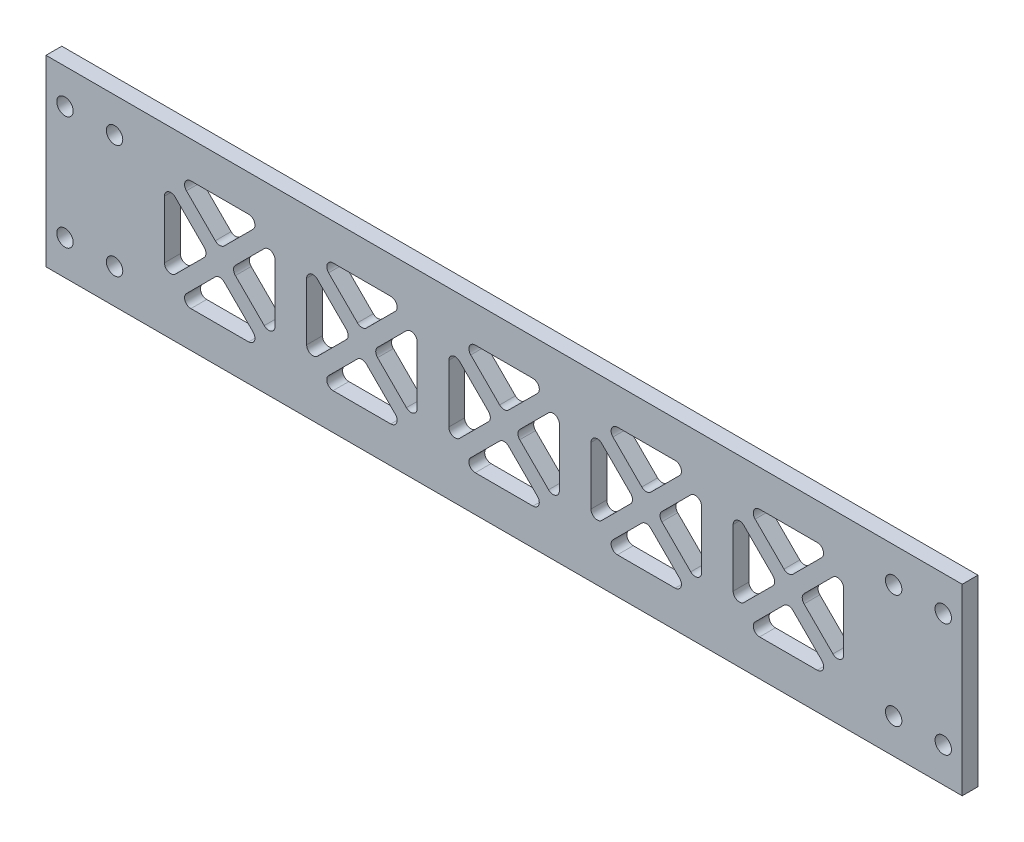
SolidWorks part; units mm, degrees
ref_plane "前视基准面" through (0, 0, 0) normal (0, 0, 1) x (1, 0, 0)
ref_plane "上视基准面" through (0, 0, 0) normal (0, 1, 0) x (1, 0, 0)
ref_plane "右视基准面" through (0, 0, 0) normal (1, 0, 0) x (0, 0, -1)
other "Configuration Table"
sketch "草图1" plane through (0, 0, 0) normal (0, 0, 1) x (1, 0, 0)
  line L1 (0, 0) -> (290, 0)
  line L2 (0, 0) -> (0, -58)
  line L3 (0, -58) -> (290, -58)
  line L4 (290, 0) -> (290, -58)
  dimension "D1" = 58
  dimension "D2" = 290
extrude "凸台-拉伸1" add sketch "草图1" along normal blind 5
sketch "草图2" plane through (0, 0, 5) normal (0, 0, 1) x (1, 0, 0)
  line L0 (145, 0) -> (145, -58)
  line L1 (0, -15) -> (-5, -15)
  line L2 (0, -15) -> (0, -43)
  line L3 (0, -43) -> (-5, -43)
  line L4 (0, 0) -> (0, -58)
  line L5 (0, -58) -> (290, -58)
  line L6 (290, -58) -> (290, 0)
  line L7 (290, 0) -> (0, 0)
  line L8 (0, 0) -> (0, -58)
  line L9 (0, -58) -> (290, -58)
  line L10 (290, -58) -> (290, 0)
  line L11 (290, 0) -> (0, 0)
  line L12 (-5, -15) -> (-5, -43)
  line L13 (290, -43) -> (295, -43)
  line L14 (295, -15) -> (295, -43)
  line L15 (290, -15) -> (295, -15)
  line L16 (290, -15) -> (290, -43)
  dimension "D2" = 28
  dimension "D3" = 15
  dimension "D4" = 5
  dimension "D1" = 0
extrude "凸台-拉伸2" add sketch "草图2" against normal blind 5 contours L15 L10 L13 L14 | L2 L3 L12 L1
sketch "草图4" plane through (0, 0, 0) normal (0, 0, -1) x (-1, 0, 0)
  line L0 (-145, 0) -> (-145, -58) construction
  line L1 (-262.3, -15) -> (-257.3, -15)
  line L2 (-262.3, -15) -> (-262.3, -43)
  line L3 (-262.3, -43) -> (-257.3, -43)
  line L4 (-257.3, -15) -> (-257.3, -43)
  line L5 (-27.7, -43) -> (-32.7, -43)
  line L6 (-32.7, -15) -> (-32.7, -43)
  line L7 (-27.7, -15) -> (-32.7, -15)
  line L8 (-27.7, -15) -> (-27.7, -43)
  line L13 (-290, -43) -> (-290, -58)
  line L14 (-290, -58) -> (0, -58)
  line L15 (0, -58) -> (0, -43)
  line L20 (0, 0) -> (-290, 0)
  line L25 (-290, -43) -> (-290, -58)
  line L26 (-290, -58) -> (0, -58)
  line L27 (0, -58) -> (0, -43)
  line L32 (0, 0) -> (-290, 0)
  line L37 (-295, -43) -> (-290, -43)
  line L38 (-295, -43) -> (-290, -43)
  line L39 (0, -43) -> (5, -43)
  line L40 (0, -43) -> (5, -43)
  line L41 (5, -43) -> (5, -15)
  line L42 (5, -43) -> (5, -15)
  line L43 (5, -15) -> (0, -15)
  line L44 (5, -15) -> (0, -15)
  line L45 (0, -15) -> (0, 0)
  line L46 (0, -15) -> (0, 0)
  line L47 (-290, 0) -> (-290, -15)
  line L48 (-290, 0) -> (-290, -15)
  line L49 (-290, -15) -> (-295, -15)
  line L50 (-290, -15) -> (-295, -15)
  line L51 (-295, -15) -> (-295, -43)
  line L52 (-295, -15) -> (-295, -43)
  circle A0 centre (-257.3, -15) radius 1
  circle A1 centre (-262.3, -15) radius 1
  circle A2 centre (-262.3, -43) radius 1
  circle A3 centre (-257.3, -43) radius 1
  circle A12 centre (-32.7, -15) radius 1
  circle A13 centre (-27.7, -15) radius 1
  circle A14 centre (-32.7, -43) radius 1
  circle A15 centre (-27.7, -43) radius 1
  dimension "D6" = 2
  dimension "D7" = 2
  dimension "D8" = 2
  dimension "D9" = 2
  dimension "D10" = 2
  dimension "D11" = 2
  dimension "D12" = 2
  dimension "D13" = 2
  dimension "D3" = 5
  dimension "D4" = 15
  dimension "D5" = 15
  dimension "D1" = 0
extrude "切除-拉伸2" cut sketch "草图4" against normal blind 5 contours L1 A1 L2 | L2 A1 L1 | A3 L4 A0 L1 A1 L2 A2 L3 | L1 A0 L4 | L4 A0 L1 | L3 A2 L2 | L2 A2 L3 | L4 A3 L3 | L3 A3 L4 | L7 A12 L6 | L6 A12 L7 | A15 L8 A13 L7 A12 L6 A14 L5 | L7 A13 L8 | L8 A13 L7 | L6 A14 L5 | L5 A14 L6 | L5 A15 L8 | L8 A15 L5
sketch "草图5" plane through (0, 0, 5) normal (0, 0, 1) x (1, 0, 0)
  line L0 (27.7, -16) -> (27.7, -42) construction
  line L1 (-5, -29) -> (295, -29)
  line L2 (145, 0) -> (145, -58)
  line L15 (290, -15) -> (290, 0)
  line L16 (290, 0) -> (0, 0)
  line L17 (0, 0) -> (0, -15)
  line L18 (290, -43) -> (295, -43)
  line L19 (290, -43) -> (295, -43)
  line L20 (295, -43) -> (295, -15)
  line L21 (295, -43) -> (295, -15)
  line L22 (0, -58) -> (290, -58)
  line L23 (295, -15) -> (290, -15)
  line L27 (290, -15) -> (290, 0)
  line L28 (290, 0) -> (0, 0)
  line L29 (0, 0) -> (0, -15)
  line L34 (0, -58) -> (290, -58)
  line L36 (295, -15) -> (290, -15)
  line L37 (0, -15) -> (-5, -15)
  line L38 (0, -15) -> (-5, -15)
  line L39 (-5, -15) -> (-5, -43)
  line L40 (-5, -15) -> (-5, -43)
  line L41 (-5, -43) -> (0, -43)
  line L42 (-5, -43) -> (0, -43)
  line L43 (0, -43) -> (0, -58)
  line L44 (0, -43) -> (0, -58)
  line L45 (290, -58) -> (290, -43)
  line L46 (290, -58) -> (290, -43)
  circle A0 centre (6, -47) radius 2.6
  circle A1 centre (21.7, -47) radius 2.6
  circle A2 centre (21.7, -11) radius 2.6
  circle A3 centre (6, -11) radius 2.6
  circle A12 centre (268.3, -47) radius 2.6
  circle A13 centre (284, -47) radius 2.6
  circle A14 centre (268.3, -11) radius 2.6
  circle A15 centre (284, -11) radius 2.6
  dimension "D2" = 11
  dimension "D3" = 11
  dimension "D4" = 5.2
  dimension "D5" = 5.2
  dimension "D7" = 6
  dimension "D1" = 0
extrude "切除-拉伸3" cut sketch "草图5" against normal through all contours A3 | A2 | A0 | A1 | A14 | A15 | A12 | A13
sketch "草图6" plane through (0, 0, 5) normal (0, 0, 1) x (1, 0, 0)
  line L4 (31.7, -15) -> (28.7, -15)
  line L5 (32.7, -42) -> (32.7, -16)
  line L6 (28.7, -43) -> (31.7, -43)
  line L7 (27.7, -16) -> (27.7, -42)
  line L8 (31.7, -15) -> (28.7, -15)
  line L9 (32.7, -42) -> (32.7, -16)
  line L10 (28.7, -43) -> (31.7, -43)
  line L11 (27.7, -16) -> (27.7, -42)
  line L12 (258.3, -43) -> (261.3, -43)
  line L13 (257.3, -16) -> (257.3, -42)
  line L14 (261.3, -15) -> (258.3, -15)
  line L15 (262.3, -42) -> (262.3, -16)
  line L16 (258.3, -43) -> (261.3, -43)
  line L17 (257.3, -16) -> (257.3, -42)
  line L18 (261.3, -15) -> (258.3, -15)
  line L19 (262.3, -42) -> (262.3, -16)
  circle A1 centre (6, -11) radius 2.6
  circle A2 centre (6, -11) radius 2.6
  circle A3 centre (284, -11) radius 2.6
  arc A4 (28.7, -15) -> (27.7, -16) centre (27.7, -15) ccw
  arc A5 (32.7, -16) -> (31.7, -15) centre (32.7, -15) ccw
  arc A6 (31.7, -43) -> (32.7, -42) centre (32.7, -43) ccw
  arc A7 (27.7, -42) -> (28.7, -43) centre (27.7, -43) ccw
  arc A8 (28.7, -15) -> (27.7, -16) centre (27.7, -15) ccw
  arc A9 (32.7, -16) -> (31.7, -15) centre (32.7, -15) ccw
  arc A10 (31.7, -43) -> (32.7, -42) centre (32.7, -43) ccw
  arc A11 (27.7, -42) -> (28.7, -43) centre (27.7, -43) ccw
  arc A12 (261.3, -43) -> (262.3, -42) centre (262.3, -43) ccw
  arc A13 (257.3, -42) -> (258.3, -43) centre (257.3, -43) ccw
  arc A14 (258.3, -15) -> (257.3, -16) centre (257.3, -15) ccw
  arc A15 (262.3, -16) -> (261.3, -15) centre (262.3, -15) ccw
  arc A16 (261.3, -43) -> (262.3, -42) centre (262.3, -43) ccw
  arc A17 (257.3, -42) -> (258.3, -43) centre (257.3, -43) ccw
  arc A18 (258.3, -15) -> (257.3, -16) centre (257.3, -15) ccw
  arc A19 (262.3, -16) -> (261.3, -15) centre (262.3, -15) ccw
  circle A20 centre (284, -11) radius 2.6
  circle A21 centre (268.3, -47) radius 2.6
  circle A22 centre (268.3, -47) radius 2.6
  circle A23 centre (284, -47) radius 2.6
  circle A24 centre (284, -47) radius 2.6
  circle A25 centre (21.7, -11) radius 2.6
  circle A26 centre (21.7, -11) radius 2.6
  circle A27 centre (6, -47) radius 2.6
  circle A28 centre (6, -47) radius 2.6
  circle A29 centre (21.7, -47) radius 2.6
  circle A30 centre (21.7, -47) radius 2.6
  circle A31 centre (268.3, -11) radius 2.6
  circle A32 centre (268.3, -11) radius 2.6
  dimension "D1" = 0
  dimension "D2" = 0
  dimension "D3" = 0
  dimension "D4" = 0
  dimension "D5" = 0
  dimension "D6" = 0
  dimension "D7" = 0
  dimension "D8" = 0
  dimension "D9" = 0
  dimension "D10" = 0
extrude "凸台-拉伸3" add sketch "草图6" against normal through all contours A8 L11 A11 L10 A10 L9 A9 L8 | A16 L19 A19 L18 A18 L17 A17 L16
sketch "草图8" plane through (0, 0, 5) normal (0, 0, 1) x (1, 0, 0)
  line L0 (-5, -29) -> (295, -29) construction
  line L1 (35, -49) -> (75, -49)
  line L2 (35, -49) -> (35, -9)
  line L3 (35, -9) -> (75, -9)
  line L4 (75, -49) -> (75, -9)
  line L5 (35, -49) -> (75, -9) construction
  line L6 (35, -9) -> (55, -29) construction
  line L7 (-5, -15) -> (-5, -43) construction
  line L8 (295, -15) -> (295, -43) construction
  line L9 (145, 0) -> (145, -58) construction
  line L10 (290, 0) -> (0, 0) construction
  line L11 (0, -58) -> (290, -58) construction
  line L12 (35, -9) -> (55, -29)
  line L13 (55, -29) -> (75, -9)
  line L14 (72.5, -19.864) -> (72.5, -38.136)
  line L15 (69.0858, -39.5503) -> (59.9497, -30.4142)
  line L16 (45.864, -11.5) -> (64.136, -11.5)
  line L17 (65.5503, -14.9142) -> (56.4142, -24.0503)
  line L18 (53.5858, -24.0503) -> (44.4497, -14.9142)
  line L19 (59.9497, -27.5858) -> (69.0858, -18.4497)
  line L20 (64.136, -46.5) -> (45.864, -46.5)
  line L21 (44.4497, -43.0858) -> (53.5858, -33.9497)
  line L22 (56.4142, -33.9497) -> (65.5503, -43.0858)
  line L23 (37.5, -38.136) -> (37.5, -19.864)
  line L24 (40.9142, -18.4497) -> (50.0503, -27.5858)
  line L25 (50.0503, -30.4142) -> (40.9142, -39.5503)
  line L26 (55, -29) -> (56.4142, -24.0503) construction
  line L27 (55, -29) -> (59.9497, -30.4142) construction
  line L28 (90.864, -11.5) -> (109.136, -11.5)
  line L29 (110.5503, -14.9142) -> (101.4142, -24.0503)
  line L30 (98.5858, -24.0503) -> (89.4497, -14.9142)
  line L31 (82.5, -38.136) -> (82.5, -19.864)
  line L32 (85.9142, -18.4497) -> (95.0503, -27.5858)
  line L33 (95.0503, -30.4142) -> (85.9142, -39.5503)
  line L34 (117.5, -19.864) -> (117.5, -38.136)
  line L35 (114.0858, -39.5503) -> (104.9497, -30.4142)
  line L36 (104.9497, -27.5858) -> (114.0858, -18.4497)
  line L37 (109.136, -46.5) -> (90.864, -46.5)
  line L38 (89.4497, -43.0858) -> (98.5858, -33.9497)
  line L39 (101.4142, -33.9497) -> (110.5503, -43.0858)
  line L40 (135.864, -11.5) -> (154.136, -11.5)
  line L41 (155.5503, -14.9142) -> (146.4142, -24.0503)
  line L42 (143.5858, -24.0503) -> (134.4497, -14.9142)
  line L43 (127.5, -38.136) -> (127.5, -19.864)
  line L44 (130.9142, -18.4497) -> (140.0503, -27.5858)
  line L45 (140.0503, -30.4142) -> (130.9142, -39.5503)
  line L46 (162.5, -19.864) -> (162.5, -38.136)
  line L47 (159.0858, -39.5503) -> (149.9497, -30.4142)
  line L48 (149.9497, -27.5858) -> (159.0858, -18.4497)
  line L49 (154.136, -46.5) -> (135.864, -46.5)
  line L50 (134.4497, -43.0858) -> (143.5858, -33.9497)
  line L51 (146.4142, -33.9497) -> (155.5503, -43.0858)
  line L52 (180.864, -11.5) -> (199.136, -11.5)
  line L53 (200.5503, -14.9142) -> (191.4142, -24.0503)
  line L54 (188.5858, -24.0503) -> (179.4497, -14.9142)
  line L55 (172.5, -38.136) -> (172.5, -19.864)
  line L56 (175.9142, -18.4497) -> (185.0503, -27.5858)
  line L57 (185.0503, -30.4142) -> (175.9142, -39.5503)
  line L58 (207.5, -19.864) -> (207.5, -38.136)
  line L59 (204.0858, -39.5503) -> (194.9497, -30.4142)
  line L60 (194.9497, -27.5858) -> (204.0858, -18.4497)
  line L61 (199.136, -46.5) -> (180.864, -46.5)
  line L62 (179.4497, -43.0858) -> (188.5858, -33.9497)
  line L63 (191.4142, -33.9497) -> (200.5503, -43.0858)
  line L64 (225.864, -11.5) -> (244.136, -11.5)
  line L65 (245.5503, -14.9142) -> (236.4142, -24.0503)
  line L66 (233.5858, -24.0503) -> (224.4497, -14.9142)
  line L67 (217.5, -38.136) -> (217.5, -19.864)
  line L68 (220.9142, -18.4497) -> (230.0503, -27.5858)
  line L69 (230.0503, -30.4142) -> (220.9142, -39.5503)
  line L70 (252.5, -19.864) -> (252.5, -38.136)
  line L71 (249.0858, -39.5503) -> (239.9497, -30.4142)
  line L72 (239.9497, -27.5858) -> (249.0858, -18.4497)
  line L73 (244.136, -46.5) -> (225.864, -46.5)
  line L74 (224.4497, -43.0858) -> (233.5858, -33.9497)
  line L75 (236.4142, -33.9497) -> (245.5503, -43.0858)
  arc A0 (65.5503, -14.9142) -> (64.136, -11.5) centre (64.136, -13.5) ccw
  arc A1 (53.5858, -24.0503) -> (56.4142, -24.0503) centre (55, -22.636) ccw
  arc A2 (44.4497, -14.9142) -> (45.864, -11.5) centre (45.864, -13.5) cw
  arc A3 (69.0858, -18.4497) -> (72.5, -19.864) centre (70.5, -19.864) cw
  arc A4 (69.0858, -39.5503) -> (72.5, -38.136) centre (70.5, -38.136) ccw
  arc A5 (59.9497, -27.5858) -> (59.9497, -30.4142) centre (61.364, -29) ccw
  arc A6 (65.5503, -43.0858) -> (64.136, -46.5) centre (64.136, -44.5) cw
  arc A7 (44.4497, -43.0858) -> (45.864, -46.5) centre (45.864, -44.5) ccw
  arc A8 (56.4142, -33.9497) -> (53.5858, -33.9497) centre (55, -35.364) ccw
  arc A9 (40.9142, -39.5503) -> (37.5, -38.136) centre (39.5, -38.136) cw
  arc A10 (40.9142, -18.4497) -> (37.5, -19.864) centre (39.5, -19.864) ccw
  arc A11 (50.0503, -30.4142) -> (50.0503, -27.5858) centre (48.636, -29) ccw
  arc A12 (89.4497, -14.9142) -> (90.864, -11.5) centre (90.864, -13.5) cw
  arc A13 (110.5503, -14.9142) -> (109.136, -11.5) centre (109.136, -13.5) ccw
  arc A14 (98.5858, -24.0503) -> (101.4142, -24.0503) centre (100, -22.636) ccw
  arc A15 (85.9142, -18.4497) -> (82.5, -19.864) centre (84.5, -19.864) ccw
  arc A16 (95.0503, -30.4142) -> (95.0503, -27.5858) centre (93.636, -29) ccw
  arc A17 (85.9142, -39.5503) -> (82.5, -38.136) centre (84.5, -38.136) cw
  arc A18 (114.0858, -39.5503) -> (117.5, -38.136) centre (115.5, -38.136) ccw
  arc A19 (104.9497, -27.5858) -> (104.9497, -30.4142) centre (106.364, -29) ccw
  arc A20 (114.0858, -18.4497) -> (117.5, -19.864) centre (115.5, -19.864) cw
  arc A21 (89.4497, -43.0858) -> (90.864, -46.5) centre (90.864, -44.5) ccw
  arc A22 (101.4142, -33.9497) -> (98.5858, -33.9497) centre (100, -35.364) ccw
  arc A23 (110.5503, -43.0858) -> (109.136, -46.5) centre (109.136, -44.5) cw
  arc A24 (134.4497, -14.9142) -> (135.864, -11.5) centre (135.864, -13.5) cw
  arc A25 (155.5503, -14.9142) -> (154.136, -11.5) centre (154.136, -13.5) ccw
  arc A26 (143.5858, -24.0503) -> (146.4142, -24.0503) centre (145, -22.636) ccw
  arc A27 (130.9142, -18.4497) -> (127.5, -19.864) centre (129.5, -19.864) ccw
  arc A28 (140.0503, -30.4142) -> (140.0503, -27.5858) centre (138.636, -29) ccw
  arc A29 (130.9142, -39.5503) -> (127.5, -38.136) centre (129.5, -38.136) cw
  arc A30 (159.0858, -39.5503) -> (162.5, -38.136) centre (160.5, -38.136) ccw
  arc A31 (149.9497, -27.5858) -> (149.9497, -30.4142) centre (151.364, -29) ccw
  arc A32 (159.0858, -18.4497) -> (162.5, -19.864) centre (160.5, -19.864) cw
  arc A33 (134.4497, -43.0858) -> (135.864, -46.5) centre (135.864, -44.5) ccw
  arc A34 (146.4142, -33.9497) -> (143.5858, -33.9497) centre (145, -35.364) ccw
  arc A35 (155.5503, -43.0858) -> (154.136, -46.5) centre (154.136, -44.5) cw
  arc A36 (179.4497, -14.9142) -> (180.864, -11.5) centre (180.864, -13.5) cw
  arc A37 (200.5503, -14.9142) -> (199.136, -11.5) centre (199.136, -13.5) ccw
  arc A38 (188.5858, -24.0503) -> (191.4142, -24.0503) centre (190, -22.636) ccw
  arc A39 (175.9142, -18.4497) -> (172.5, -19.864) centre (174.5, -19.864) ccw
  arc A40 (185.0503, -30.4142) -> (185.0503, -27.5858) centre (183.636, -29) ccw
  arc A41 (175.9142, -39.5503) -> (172.5, -38.136) centre (174.5, -38.136) cw
  arc A42 (204.0858, -39.5503) -> (207.5, -38.136) centre (205.5, -38.136) ccw
  arc A43 (194.9497, -27.5858) -> (194.9497, -30.4142) centre (196.364, -29) ccw
  arc A44 (204.0858, -18.4497) -> (207.5, -19.864) centre (205.5, -19.864) cw
  arc A45 (179.4497, -43.0858) -> (180.864, -46.5) centre (180.864, -44.5) ccw
  arc A46 (191.4142, -33.9497) -> (188.5858, -33.9497) centre (190, -35.364) ccw
  arc A47 (200.5503, -43.0858) -> (199.136, -46.5) centre (199.136, -44.5) cw
  arc A48 (224.4497, -14.9142) -> (225.864, -11.5) centre (225.864, -13.5) cw
  arc A49 (245.5503, -14.9142) -> (244.136, -11.5) centre (244.136, -13.5) ccw
  arc A50 (233.5858, -24.0503) -> (236.4142, -24.0503) centre (235, -22.636) ccw
  arc A51 (220.9142, -18.4497) -> (217.5, -19.864) centre (219.5, -19.864) ccw
  arc A52 (230.0503, -30.4142) -> (230.0503, -27.5858) centre (228.636, -29) ccw
  arc A53 (220.9142, -39.5503) -> (217.5, -38.136) centre (219.5, -38.136) cw
  arc A54 (249.0858, -39.5503) -> (252.5, -38.136) centre (250.5, -38.136) ccw
  arc A55 (239.9497, -27.5858) -> (239.9497, -30.4142) centre (241.364, -29) ccw
  arc A56 (249.0858, -18.4497) -> (252.5, -19.864) centre (250.5, -19.864) cw
  arc A57 (224.4497, -43.0858) -> (225.864, -46.5) centre (225.864, -44.5) ccw
  arc A58 (236.4142, -33.9497) -> (233.5858, -33.9497) centre (235, -35.364) ccw
  arc A59 (245.5503, -43.0858) -> (244.136, -46.5) centre (244.136, -44.5) cw
  point P0 (55, -29)
  dimension "D7" = 2
  dimension "D1" = 40
  dimension "D2" = 40
  dimension "D3" = 2.5
  dimension "D4" = 2.5
  dimension "D5" = 2.5
  dimension "D9" = 90
  dimension "D10" = 5.1478
  dimension "D12" = 45
  dimension "D11" = 5
  dimension "D8" = 4
extrude "切除-拉伸5" cut sketch "草图8" against normal blind 10 contours A2 L18 A1 L17 A0 L16 | L25 A11 L24 A10 L23 A9 | L19 A5 L15 A4 L14 A3 | L22 A8 L21 A7 L20 A6 | A23 L39 A22 L38 A21 L37 | A17 L33 A16 L32 A15 L31 | L30 A14 L29 A13 L28 A12 | A20 L36 A19 L35 A18 L34 | A29 L45 A28 L44 A27 L43 | L42 A26 L41 A25 L40 A24 | A32 L48 A31 L47 A30 L46 | A35 L51 A34 L50 A33 L49 | L54 A38 L53 A37 L52 A36 | A41 L57 A40 L56 A39 L55 | A44 L60 A43 L59 A42 L58 | A47 L63 A46 L62 A45 L61 | A53 L69 A52 L68 A51 L67 | L66 A50 L65 A49 L64 A48 | A56 L72 A55 L71 A54 L70 | A59 L75 A58 L74 A57 L73
sketch "草图7" plane through (0, 0, 5) normal (0, 0, 1) x (1, 0, 0)
  line L0 (-5, -29) -> (295, -29)
  line L1 (6, -11) -> (21.7, -47)
  line L2 (145, 0) -> (145, -58)
  line L3 (13.85, -14) -> (0.8596, -21.5)
  line L4 (0.8596, -21.5) -> (0.8596, -36.5)
  line L5 (0.8596, -36.5) -> (13.85, -44)
  line L6 (13.85, -44) -> (26.8404, -36.5)
  line L7 (26.8404, -36.5) -> (26.8404, -21.5)
  line L8 (26.8404, -21.5) -> (13.85, -14)
  line L9 (276.15, -14) -> (289.1404, -21.5)
  line L10 (289.1404, -36.5) -> (276.15, -44)
  line L11 (289.1404, -21.5) -> (289.1404, -36.5)
  line L15 (290, -15) -> (290, 0)
  line L16 (290, 0) -> (0, 0)
  line L17 (0, 0) -> (0, -15)
  line L22 (0, -58) -> (290, -58)
  line L27 (290, -15) -> (290, 0)
  line L28 (290, 0) -> (0, 0)
  line L29 (0, 0) -> (0, -15)
  line L34 (0, -58) -> (290, -58)
  line L36 (276.15, -44) -> (263.1596, -36.5)
  line L37 (263.1596, -36.5) -> (263.1596, -21.5)
  line L38 (263.1596, -21.5) -> (276.15, -14)
  line L39 (90.92, -10) -> (120.92, -10) construction
  line L40 (90.92, -5) -> (120.92, -5)
  line L41 (90.92, -15) -> (120.92, -15)
  line L42 (51.8404, -29) -> (81.8404, -29) construction
  line L43 (51.8404, -24) -> (81.8404, -24)
  line L44 (51.8404, -34) -> (81.8404, -34)
  line L45 (130, -29) -> (160, -29) construction
  line L46 (130, -24) -> (160, -24)
  line L47 (130, -34) -> (160, -34)
  line L48 (90.92, -48) -> (120.92, -48) construction
  line L49 (90.92, -53) -> (120.92, -53)
  line L50 (90.92, -43) -> (120.92, -43)
  line L51 (32.7604, -10) -> (42.7604, -10) construction
  line L52 (32.7604, -5) -> (42.7604, -5)
  line L53 (32.7604, -15) -> (42.7604, -15)
  line L54 (32.7604, -48) -> (42.7604, -48) construction
  line L55 (32.7604, -53) -> (42.7604, -53)
  line L56 (32.7604, -43) -> (42.7604, -43)
  line L57 (199.08, -48) -> (169.08, -48) construction
  line L58 (199.08, -53) -> (169.08, -53)
  line L59 (199.08, -43) -> (169.08, -43)
  line L60 (199.08, -10) -> (169.08, -10) construction
  line L61 (199.08, -5) -> (169.08, -5)
  line L62 (199.08, -15) -> (169.08, -15)
  line L63 (238.1596, -29) -> (208.1596, -29) construction
  line L64 (238.1596, -24) -> (208.1596, -24)
  line L65 (238.1596, -34) -> (208.1596, -34)
  line L66 (257.2396, -48) -> (247.2396, -48) construction
  line L67 (257.2396, -53) -> (247.2396, -53)
  line L68 (257.2396, -43) -> (247.2396, -43)
  line L69 (257.2396, -10) -> (247.2396, -10) construction
  line L70 (257.2396, -5) -> (247.2396, -5)
  line L71 (257.2396, -15) -> (247.2396, -15)
  line L76 (290, -43) -> (295, -43)
  line L77 (290, -43) -> (295, -43)
  line L78 (295, -43) -> (295, -15)
  line L79 (295, -43) -> (295, -15)
  line L80 (295, -15) -> (290, -15)
  line L81 (295, -15) -> (290, -15)
  line L82 (0, -15) -> (-5, -15)
  line L83 (0, -15) -> (-5, -15)
  line L84 (-5, -15) -> (-5, -43)
  line L85 (-5, -15) -> (-5, -43)
  line L86 (-5, -43) -> (0, -43)
  line L87 (-5, -43) -> (0, -43)
  line L88 (0, -43) -> (0, -58)
  line L89 (0, -43) -> (0, -58)
  line L90 (290, -58) -> (290, -43)
  line L91 (290, -58) -> (290, -43)
  circle A0 centre (13.85, -29) radius 12.9904 construction
  circle A1 centre (276.15, -29) radius 12.9904 construction
  arc A2 (90.92, -5) -> (90.92, -15) centre (90.92, -10) ccw
  arc A3 (120.92, -15) -> (120.92, -5) centre (120.92, -10) ccw
  arc A12 (51.8404, -24) -> (51.8404, -34) centre (51.8404, -29) ccw
  arc A13 (81.8404, -34) -> (81.8404, -24) centre (81.8404, -29) ccw
  arc A14 (130, -24) -> (130, -34) centre (130, -29) ccw
  arc A15 (160, -34) -> (160, -24) centre (160, -29) ccw
  arc A16 (90.92, -53) -> (90.92, -43) centre (90.92, -48) cw
  arc A17 (120.92, -43) -> (120.92, -53) centre (120.92, -48) cw
  circle A18 centre (145, -10) radius 5
  circle A19 centre (105.92, -29) radius 5
  circle A20 centre (66.8404, -10) radius 5
  arc A21 (32.7604, -5) -> (32.7604, -15) centre (32.7604, -10) ccw
  arc A22 (42.7604, -15) -> (42.7604, -5) centre (42.7604, -10) ccw
  circle A23 centre (66.8404, -48) radius 5
  arc A24 (32.7604, -53) -> (32.7604, -43) centre (32.7604, -48) cw
  arc A25 (42.7604, -43) -> (42.7604, -53) centre (42.7604, -48) cw
  circle A26 centre (145, -48) radius 5
  arc A27 (199.08, -53) -> (199.08, -43) centre (199.08, -48) ccw
  arc A28 (169.08, -43) -> (169.08, -53) centre (169.08, -48) ccw
  circle A29 centre (184.08, -29) radius 5
  arc A30 (199.08, -5) -> (199.08, -15) centre (199.08, -10) cw
  arc A31 (169.08, -15) -> (169.08, -5) centre (169.08, -10) cw
  circle A32 centre (223.1596, -10) radius 5
  arc A33 (238.1596, -24) -> (238.1596, -34) centre (238.1596, -29) cw
  arc A34 (208.1596, -34) -> (208.1596, -24) centre (208.1596, -29) cw
  circle A35 centre (223.1596, -48) radius 5
  arc A36 (257.2396, -53) -> (257.2396, -43) centre (257.2396, -48) ccw
  arc A37 (247.2396, -43) -> (247.2396, -53) centre (247.2396, -48) ccw
  arc A38 (257.2396, -5) -> (257.2396, -15) centre (257.2396, -10) cw
  arc A39 (247.2396, -15) -> (247.2396, -5) centre (247.2396, -10) cw
  point P16 (13.85, -29)
  point P47 (105.92, -10)
  point P54 (145, -29)
  point P57 (66.8404, -29)
  point P69 (105.92, -48)
  point P79 (37.7604, -10)
  point P90 (37.7604, -48)
  point P99 (184.08, -48)
  point P108 (184.08, -10)
  point P117 (223.1596, -29)
  point P126 (252.2396, -48)
  point P133 (252.2396, -10)
  dimension "D4" = 5
  dimension "D8" = 5
  dimension "D11" = 5
  dimension "D13" = 10
  dimension "D5" = 10
  dimension "D14" = 10
  dimension "D15" = 5
  dimension "D2" = 15
  dimension "D3" = 5
  dimension "D6" = 30
  dimension "D7" = 30
  dimension "D9" = 25
  dimension "D10" = 30
  dimension "D12" = 24.08
  dimension "D16" = 24.08
  dimension "D17" = 10
  dimension "D1" = 0
extrude "切除-拉伸4" [suppressed] cut sketch "草图7" against normal blind 10 contours A20 | L53 A22 L52 A21 | L7 L8 L3 L1 L0 | L6 L7 L0 L1 | L5 L6 L1 L0 L4 | L3 L4 L0 L1 | A25 L56 A24 L55 | A23 | L44 A13 L0 A12 | L0 A13 L43 A12 | A17 L50 A16 L49 | L41 A3 L40 A2 | L0 A19 | L0 A19 | L0 A15 L46 L2 | L2 A18 | L2 A18 | L46 A14 L0 L2 | L0 A14 L47 L2 | L47 A15 L0 L2 | A26 L2 | A26 L2 | L59 A28 L58 A27 | A31 L62 A30 L61 | A29 L0 | A29 L0 | A34 L65 A33 L0 | A34 L0 A33 L64 | A32 | A35 | L68 A37 L67 A36 | A39 L71 A38 L70 | L38 L37 L0 L11 L9 | L37 L36 L10 L11 L0
sketch "草图9" plane through (0, 0, 5) normal (0, 0, 1) x (1, 0, 0)
  line L0 (0, -15) -> (0, -43)
  line L1 (290, -15) -> (290, -43)
  line L12 (0, 0) -> (0, -15)
  line L13 (0, -15) -> (-5, -15)
  line L14 (-5, -15) -> (-5, -43)
  line L15 (-5, -43) -> (0, -43)
  line L16 (0, -43) -> (0, -58)
  line L17 (0, -58) -> (290, -58)
  line L18 (290, -58) -> (290, -43)
  line L19 (290, -43) -> (295, -43)
  line L20 (295, -43) -> (295, -15)
  line L21 (295, -15) -> (290, -15)
  line L22 (290, -15) -> (290, 0)
  line L23 (290, 0) -> (0, 0)
  line L24 (0, 0) -> (0, -15)
  line L25 (0, -15) -> (-5, -15)
  line L26 (-5, -15) -> (-5, -43)
  line L27 (-5, -43) -> (0, -43)
  line L28 (0, -43) -> (0, -58)
  line L29 (0, -58) -> (290, -58)
  line L30 (290, -58) -> (290, -43)
  line L31 (290, -43) -> (295, -43)
  line L32 (295, -43) -> (295, -15)
  line L33 (295, -15) -> (290, -15)
  line L34 (290, -15) -> (290, 0)
  line L35 (290, 0) -> (0, 0)
  dimension "D1" = 0
extrude "切除-拉伸6" cut sketch "草图9" against normal blind 10 contours L26 L27 L0 L25 | L32 L33 L1 L31
